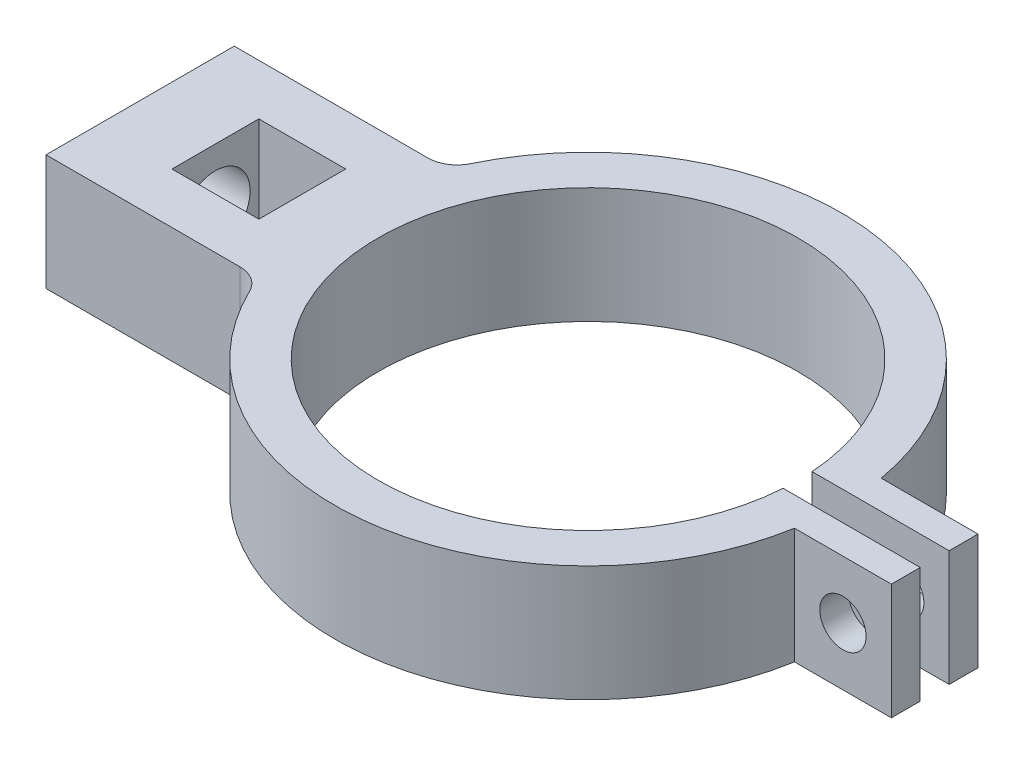
SolidWorks part; units mm, degrees
ref_plane "Front Plane" through (0, 0, 0) normal (0, 0, 1) x (1, 0, 0)
ref_plane "Top Plane" through (0, 0, 0) normal (0, 1, 0) x (1, 0, 0)
ref_plane "Right Plane" through (0, 0, 0) normal (1, 0, 0) x (0, 0, -1)
sketch "Sketch1" plane through (0, 0, 0) normal (0, 1, 0) x (1, 0, 0)
  line L1 (30.3912, 3.8096) -> (30.3936, 1.2787)
  line L3 (21.8961, 3.8096) -> (30.3912, 3.8096)
  line L6 (21.8991, -3.7923) -> (30.3942, -3.7923)
  line L16 (-39.292, 8.255) -> (-39.292, -8.255)
  line L17 (-20.6351, 8.255) -> (-39.292, 8.255)
  line L18 (-20.6351, -8.255) -> (-39.292, -8.255)
  line L19 (30.3948, -1.2613) -> (18.3718, -1.2613)
  line L20 (30.3936, 1.2787) -> (18.3706, 1.2787)
  line L22 (-32.688, -3.8104) -> (-25.068, -3.8104)
  line L23 (-32.688, -3.8104) -> (-32.688, 3.8096)
  line L24 (-32.688, 3.8096) -> (-25.068, 3.8096)
  line L25 (30.3948, -1.2613) -> (30.3942, -3.7923)
  line L26 (-25.068, -3.8104) -> (-25.068, 3.8096)
  line L27 (-32.688, -3.8104) -> (-25.068, 3.8096) construction
  line L28 (-32.688, 3.8096) -> (-25.068, -3.8104) construction
  arc A1 (21.8961, 3.8096) -> (-20.6351, 8.255) centre (0, 0) ccw
  arc A3 (18.3706, 1.2787) -> (18.3718, -1.2613) centre (0, 0) ccw
  arc A4 (-20.6351, -8.255) -> (21.8991, -3.7923) centre (0, 0) ccw
  point P0 (-28.878, -0.0004)
  dimension "D1" = 16.51
  dimension "D2" = 6.604
  dimension "D3" = 7.62
  dimension "D4" = 7.62
  dimension "D5" = 8.4951
extrude "Boss-Extrude3" add sketch "Sketch1" along normal blind 10.16
sketch "Sketch5" plane through (0, 0, -3.8096) normal (0, 0, -1) x (-1, 0, 0)
  circle A0 centre (-26.1451, 5.08) radius 2.032
  dimension "D1" = 4.064
extrude "Cut-Extrude1" cut sketch "Sketch5" against normal up to surface (7.6019 mm away) up to face at (26.1466, 5.08, 3.7923)
sketch "Sketch6" plane through (-39.292, 0, 0) normal (-1, 0, 0) x (0, 0, 1)
  circle A0 centre (0, 5.08) radius 3.048
extrude "Cut-Extrude2" cut sketch "Sketch6" against normal up to surface (6.604 mm away) up to face at (-32.688, 5.08, 0.0004)
fillet "Fillet1" radius 2.54 2 edges at (-20.6351, 5.08, -8.255) (-20.6351, 5.08, 8.255)
